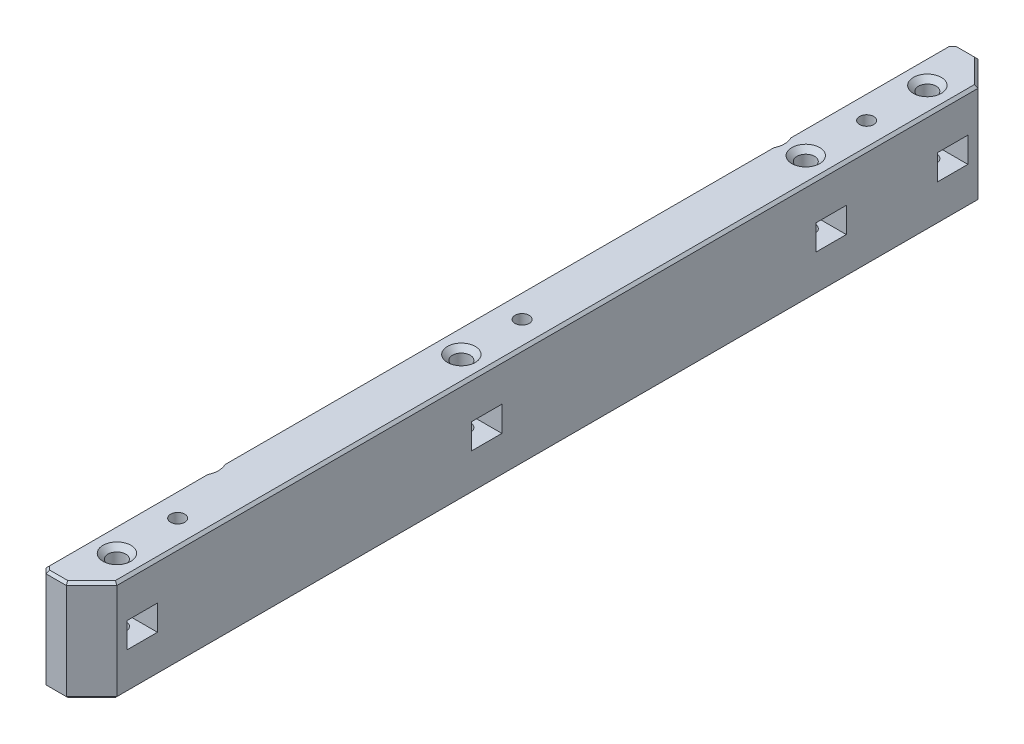
SolidWorks part; units mm, degrees
material "ABS"
ref_plane "Front Plane" through (0, 0, 0) normal (0, 0, 1) x (1, 0, 0)
ref_plane "Top Plane" through (0, 0, 0) normal (0, 1, 0) x (1, 0, 0)
ref_plane "Right Plane" through (0, 0, 0) normal (1, 0, 0) x (0, 0, -1)
sketch "Sketch1" plane through (0, 0, 0) normal (0, 0, 1) x (1, 0, 0)
  line L1 (5, -10) -> (-5, -10)
  line L2 (5, -10) -> (5, 10)
  line L3 (5, 10) -> (-5, 10)
  line L4 (-5, -10) -> (-5, 10)
  line L5 (5, -10) -> (-5, 10) construction
  line L6 (5, 10) -> (-5, -10) construction
  point P0 (0, 0)
  dimension "D1" = 10
  dimension "D2" = 20
extrude "Boss-Extrude1" add sketch "Sketch1" along normal mid plane 180
sketch "Sketch6" plane through (0, -10, 0) normal (0, -1, 0) x (1, 0, 0)
  line L0 (0, 80) -> (0, -80) construction
  circle A0 centre (0, 80) radius 1.75
  circle A1 centre (0, -80) radius 1.75
  circle A2 centre (0, 12) radius 1.75
  circle A3 centre (0, -56) radius 1.75
  dimension "D1" = 3.5
  dimension "D2" = 68
  dimension "D3" = 68
extrude "Cut-Extrude4" cut sketch "Sketch6" against normal through all
sketch "Sketch7" plane through (0, 10, 0) normal (0, 1, 0) x (1, 0, 0)
  circle A0 centre (0, 68) radius 1.4
  circle A1 centre (0, 0) radius 1.4
  circle A2 centre (0, -68) radius 1.4
  dimension "D1" = 2.8
extrude "Cut-Extrude5" cut sketch "Sketch7" against normal through all
sketch "Sketch9" plane through (0, 10, 0) normal (0, 1, 0) x (1, 0, 0)
  line L0 (5, 90) -> (-5, 90) construction
  line L1 (2.5981, -78.5) -> (1.7321, -77) construction
  line L2 (1.7321, -77) -> (-1.7321, -77)
  line L3 (-1.7321, -77) -> (-3.4641, -80)
  line L4 (-3.4641, -80) -> (-1.7321, -83)
  line L5 (-1.7321, -83) -> (1.7321, -83)
  line L6 (1.7321, -83) -> (2.5981, -81.5) construction
  line L7 (-3.4641, 80) -> (-1.7321, 77)
  line L8 (-1.7321, 77) -> (1.7321, 77)
  line L9 (1.7321, 77) -> (2.5981, 78.5) construction
  line L10 (3.4641, 80) -> (2.5981, 81.5) construction
  line L11 (1.7321, 83) -> (-1.7321, 83)
  line L12 (-1.7321, 83) -> (-3.4641, 80)
  line L13 (1.7321, 83) -> (12.7569, 83)
  line L15 (12.7569, 83) -> (12.7569, 77)
  line L16 (12.7569, 77) -> (1.7321, 77)
  line L17 (1.7321, -77) -> (12.7569, -77)
  line L18 (12.7569, -77) -> (12.7569, -83)
  line L19 (12.7569, -83) -> (1.7321, -83)
  line L20 (3.4641, -80) -> (2.5981, -78.5) construction
  line L21 (2.5981, -81.5) -> (3.4641, -80) construction
  line L22 (2.5981, 81.5) -> (1.7321, 83) construction
  line L23 (2.5981, 78.5) -> (3.4641, 80) construction
  line L24 (1.7321, -9) -> (-1.7321, -9)
  line L25 (-1.7321, -9) -> (-3.4641, -12)
  line L26 (-3.4641, -12) -> (-1.7321, -15)
  line L27 (-1.7321, -15) -> (1.7321, -15)
  line L28 (1.7321, -9) -> (12.7569, -9)
  line L29 (12.7569, -9) -> (12.7569, -15)
  line L30 (12.7569, -15) -> (1.7321, -15)
  line L31 (2.5981, -10.5) -> (1.7321, -9) construction
  line L32 (1.7321, -15) -> (2.5981, -13.5) construction
  line L33 (3.4641, -12) -> (2.5981, -10.5) construction
  line L34 (2.5981, -13.5) -> (3.4641, -12) construction
  line L35 (1.7321, 59) -> (-1.7321, 59)
  line L36 (-1.7321, 59) -> (-3.4641, 56)
  line L37 (-3.4641, 56) -> (-1.7321, 53)
  line L38 (-1.7321, 53) -> (1.7321, 53)
  line L39 (1.7321, 59) -> (12.7569, 59)
  line L40 (12.7569, 59) -> (12.7569, 53)
  line L41 (12.7569, 53) -> (1.7321, 53)
  line L42 (2.5981, 57.5) -> (1.7321, 59) construction
  line L43 (1.7321, 53) -> (2.5981, 54.5) construction
  line L44 (3.4641, 56) -> (2.5981, 57.5) construction
  line L45 (2.5981, 54.5) -> (3.4641, 56) construction
  circle A0 centre (0, -80) radius 3 construction
  circle A1 centre (0, 80) radius 3 construction
  circle A2 centre (0, -12) radius 3 construction
  circle A3 centre (0, 56) radius 3 construction
  dimension "D1" = 6
  dimension "D2" = 3
extrude "Cut-Extrude6" cut sketch "Sketch9" against normal mid plane 5 from offset 10 offset against normal yes
chamfer "Chamfer2" distance 5 angle 45 2 edges at (5, 0, -90) (5, 0, 90)
chamfer "Chamfer3" distance 1 angle 45 9 edges at (1.75, -10, -80) (0, -10, 1.4) (0, -10, 69.4) (1.75, 10, 80) (1.75, 10, -80) (-5, 0, -90) (-5, 0, 90) (1.75, 10, -56) (1.75, 10, 12)
chamfer "Chamfer4" distance 0.5 angle 45 8 edges at (-4.5, -10, 89.5) (-2, -10, 90) (2.5, -10, 87.5) (5, -10, 0) (2.5, -10, -87.5) (-2, -10, -90) (-4.5, -10, -89.5) (-5, -10, 0)
chamfer "Chamfer5" distance 0.5 angle 45 8 edges at (2.5, 10, -87.5) (5, 10, 0) (2.5, 10, 87.5) (-2, 10, 90) (-4.5, 10, 89.5) (-5, 10, 0) (-4.5, 10, -89.5) (-2, 10, -90)
sketch "Sketch10" plane through (0, -10, 0) normal (0, -1, 0) x (1, 0, 0)
  circle A0 centre (-7.8485, -55.8836) radius 3.75
  circle A1 centre (-7.8485, 55.8836) radius 3.75
  dimension "D1" = 7.5
extrude "Cut-Extrude7" cut sketch "Sketch10" against normal through all
ref_plane "Plane1" through (-10, 0, 0) normal (1, 0, 0) x (0, 0, -1)
